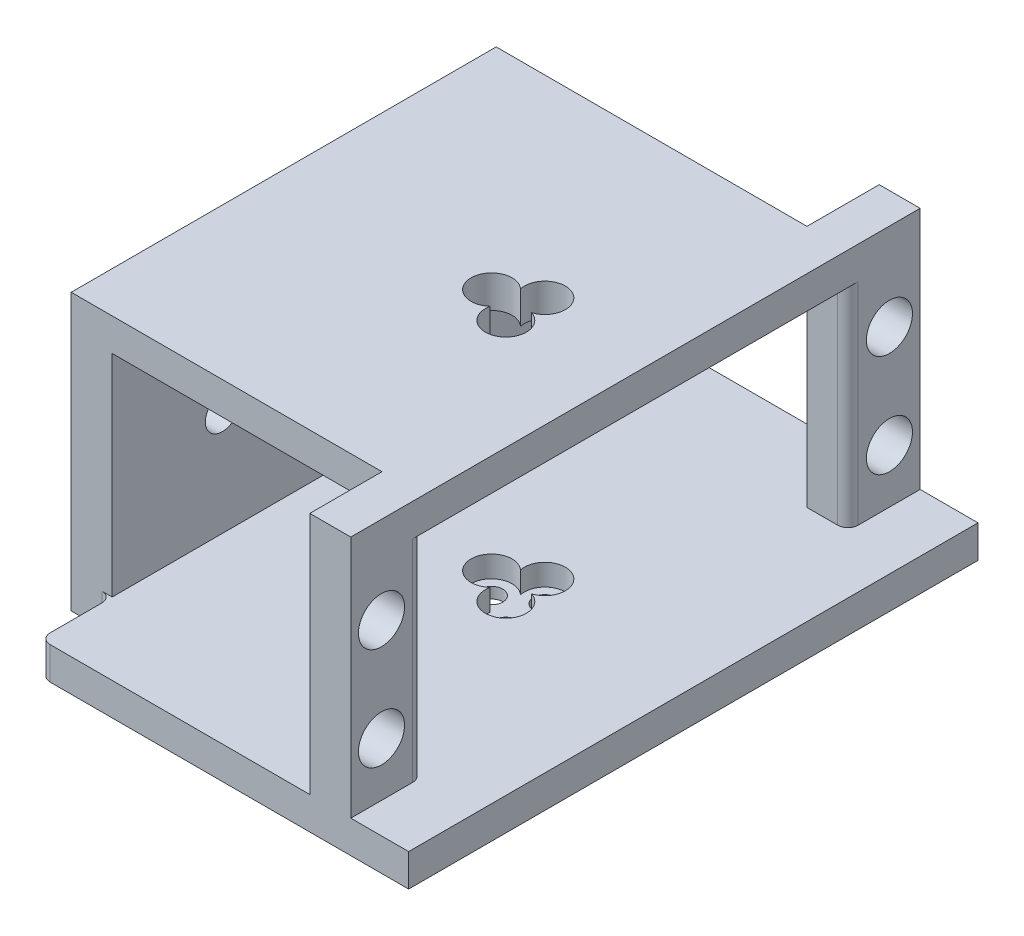
SolidWorks part; units mm, degrees
ref_plane "Front Plane" through (0, 0, 0) normal (0, 0, 1) x (1, 0, 0)
ref_plane "Top Plane" through (0, 0, 0) normal (0, 1, 0) x (1, 0, 0)
ref_plane "Right Plane" through (0, 0, 0) normal (1, 0, 0) x (0, 0, -1)
sketch "Sketch1" plane through (0, 0, 0) normal (0, 1, 0) x (1, 0, 0)
  line L1 (-20, 27.8) -> (20, 27.8)
  line L2 (-20, 27.8) -> (-20, -27.8)
  line L3 (-20, -27.8) -> (20, -27.8)
  line L4 (20, 27.8) -> (20, -27.8)
  line L5 (-20, 27.8) -> (20, -27.8) construction
  line L6 (-20, -27.8) -> (20, 27.8) construction
  point P0 (0, 0)
  dimension "D1" = 55.6
  dimension "D2" = 40
extrude "Boss-Extrude1" add sketch "Sketch1" along normal blind 3.175
sketch "Sketch2" plane through (0, 3.175, 0) normal (0, 1, 0) x (1, 0, 0)
  line L0 (-20, 27.8) -> (-20, -27.8) construction
  line L1 (-16, 20.75) -> (-20, 20.75)
  line L2 (-16, 20.75) -> (-16, -20.75)
  line L3 (-16, -20.75) -> (-20, -20.75)
  line L4 (-20, 20.75) -> (-20, -20.75)
  line L5 (-16, 20.75) -> (-20, -20.75) construction
  line L6 (-16, -20.75) -> (-20, 20.75) construction
  line L8 (-20, -27.8) -> (20, -27.8) construction
  line L9 (-20, 0) -> (65.8452, 0) construction
  line L12 (10.35, 27.8) -> (10.35, 20.75)
  line L13 (14.35, -27.8) -> (10.35, -27.8)
  line L14 (14.35, -27.8) -> (14.35, -20.75)
  line L15 (14.35, -20.75) -> (10.35, -20.75)
  line L16 (10.35, -27.8) -> (10.35, -20.75)
  line L17 (14.35, 20.75) -> (10.35, 20.75)
  line L18 (14.35, 27.8) -> (14.35, 20.75)
  line L19 (14.35, 27.8) -> (10.35, 27.8)
  line L27 (-5.55, 20.1) -> (14.25, 20.1) construction
  line L28 (-5.55, -20.1) -> (14.25, -20.1) construction
  line L30 (20, -27.8) -> (20, 27.8) construction
  point P0 (-18, 0)
  dimension "D1" = 4
  dimension "D4" = 4
  dimension "D6" = 7.05
  dimension "D9" = 41.5
  dimension "D2" = 41.5
  dimension "D3" = 0.65
  dimension "D7" = 0.65
  dimension "D5" = 5.65
extrude "Boss-Extrude2" add sketch "Sketch2" along normal blind 20.6
sketch "Sketch3" plane through (0, 23.775, 0) normal (0, 1, 0) x (1, 0, 0)
  line L0 (-20, 20.75) -> (10.35, 20.75)
  line L16 (14.35, -27.8) -> (10.35, -27.8)
  line L17 (10.35, -27.8) -> (10.35, -20.75)
  line L18 (10.35, -20.75) -> (-20, -20.75)
  line L19 (-20, -20.75) -> (-20, 20.75)
  line L20 (10.35, 20.75) -> (10.35, 27.8)
  line L21 (10.35, 27.8) -> (14.35, 27.8)
  line L22 (14.35, 27.8) -> (14.35, -27.8)
extrude "Boss-Extrude3" add sketch "Sketch3" along normal blind 3.175
sketch "Sketch5" plane through (14.35, 0, 0) normal (1, 0, 0) x (0, 0, -1)
  line L0 (-27.8, 26.95) -> (-27.8, 3.175) construction
  line L1 (-27.8, 3.175) -> (-20.75, 3.175) construction
  line L2 (0, 0) -> (0, 26.95) construction
  line L3 (-27.8, 26.95) -> (27.8, 26.95) construction
  circle A0 centre (-24.8, 8.425) radius 2.25
  circle A1 centre (-24.8, 18.425) radius 2.25
  circle A2 centre (24.8, 18.425) radius 2.25
  circle A3 centre (24.8, 8.425) radius 2.25
  dimension "D1" = 4.5
  dimension "D3" = 5.25
  dimension "D2" = 3
  dimension "D4" = 10
extrude "Cut-Extrude2" cut sketch "Sketch5" against normal up to surface (4 mm away) up to face at (10.35, 16.805, 23.57)
sketch "Sketch6" plane through (-20, 0, 0) normal (-1, 0, 0) x (0, 0, 1)
  circle A0 centre (10, 13.43) radius 1.65
  dimension "D1" = 3.3
extrude "Cut-Extrude3" cut sketch "Sketch6" against normal up to surface (4 mm away) contours A0 up to face at (-16, 13.475, 0)
fillet "Fillet1" radius 1 2 edges at (14.35, 13.475, 20.75) (14.35, 13.475, -20.75)
sketch "Sketch7" plane through (0, 3.175, 0) normal (0, 1, 0) x (1, 0, 0)
  line L1 (-20, -27.8) -> (-16, -27.8)
  line L2 (-20, -27.8) -> (-20, -20.75)
  line L3 (-20, -20.75) -> (-16, -20.75)
  line L4 (-16, -27.8) -> (-16, -20.75)
  line L5 (-20, 27.8) -> (-16, 27.8)
  line L6 (-20, 27.8) -> (-20, 20.75)
  line L7 (-20, 20.75) -> (-16, 20.75)
  line L8 (-16, 27.8) -> (-16, 20.75)
extrude "Cut-Extrude4" cut sketch "Sketch7" against normal up to surface (3.175 mm away) up to face at (0, 0, 0)
fillet "Fillet2" radius 1 4 edges at (-16, 1.5875, 27.8) (-16, 1.5875, 20.75) (-16, 1.5875, -20.75) (-16, 1.5875, -27.8)
sketch "Sketch8" plane through (0, 0, 0) normal (0, -1, 0) x (1, 0, 0)
  line L0 (-20, 0) -> (20, 0) construction
  line L1 (-20, -20.75) -> (-20, 20.75) construction
  line L2 (20, 27.8) -> (20, -27.8) construction
  line L3 (2.5, 27.8) -> (2.5, -27.8) construction
  line L5 (-15, 27.8) -> (20, 27.8) construction
  line L6 (20, -27.8) -> (-15, -27.8) construction
  line L7 (3.6, -1.9053) -> (3.6, 1.9053) construction
  line L8 (3.6, 1.9053) -> (0.3, 0) construction
  line L9 (0.3, 0) -> (3.6, -1.9053) construction
  circle A0 centre (2.5, 0) radius 4 construction
  circle A3 centre (2.5, 0) radius 1.1 construction
  circle A4 centre (3.6, 1.9053) radius 1.1
  circle A5 centre (3.6, -1.9053) radius 1.1
  circle A6 centre (0.3, 0) radius 1.1
  dimension "D1" = 8
  dimension "D2" = 2.2
  dimension "D3" = 2.2
extrude "Cut-Extrude6" cut sketch "Sketch8" against normal up to surface (3.175 mm away) up to face at (0.2688, 3.175, 0)
sketch "Sketch9" plane through (0, 3.175, 0) normal (0, 1, 0) x (1, 0, 0)
  arc A2 (1.6459, -1.4794) -> (4.2083, 0) centre (3.6, -1.9053) ccw
  arc A3 (4.2083, 0) -> (1.6459, 1.4794) centre (3.6, 1.9053) ccw
  arc A5 (1.6459, 1.4794) -> (1.6459, -1.4794) centre (0.3, 0) ccw
  dimension "D1" = 4
extrude "Cut-Extrude7" cut sketch "Sketch9" against normal blind 2.1
sketch "Sketch10" plane through (0, 3.175, 0) normal (0, 1, 0) x (1, 0, 0)
  arc A0 (1.6459, -1.4794) -> (4.2083, 0) centre (3.6, -1.9053) ccw
  arc A1 (4.2083, 0) -> (1.6459, 1.4794) centre (3.6, 1.9053) ccw
  arc A4 (1.6459, 1.4794) -> (1.6459, -1.4794) centre (0.3, 0) ccw
extrude "Cut-Extrude8" cut sketch "Sketch10" along normal up to surface (23.775 mm away) up to face at (3.7625, 26.95, 0)
equation "\"D4@Sketch2\"=\"D1@Sketch2\""
equation "\"D2@Sketch2\"=\"D9@Sketch2\""
